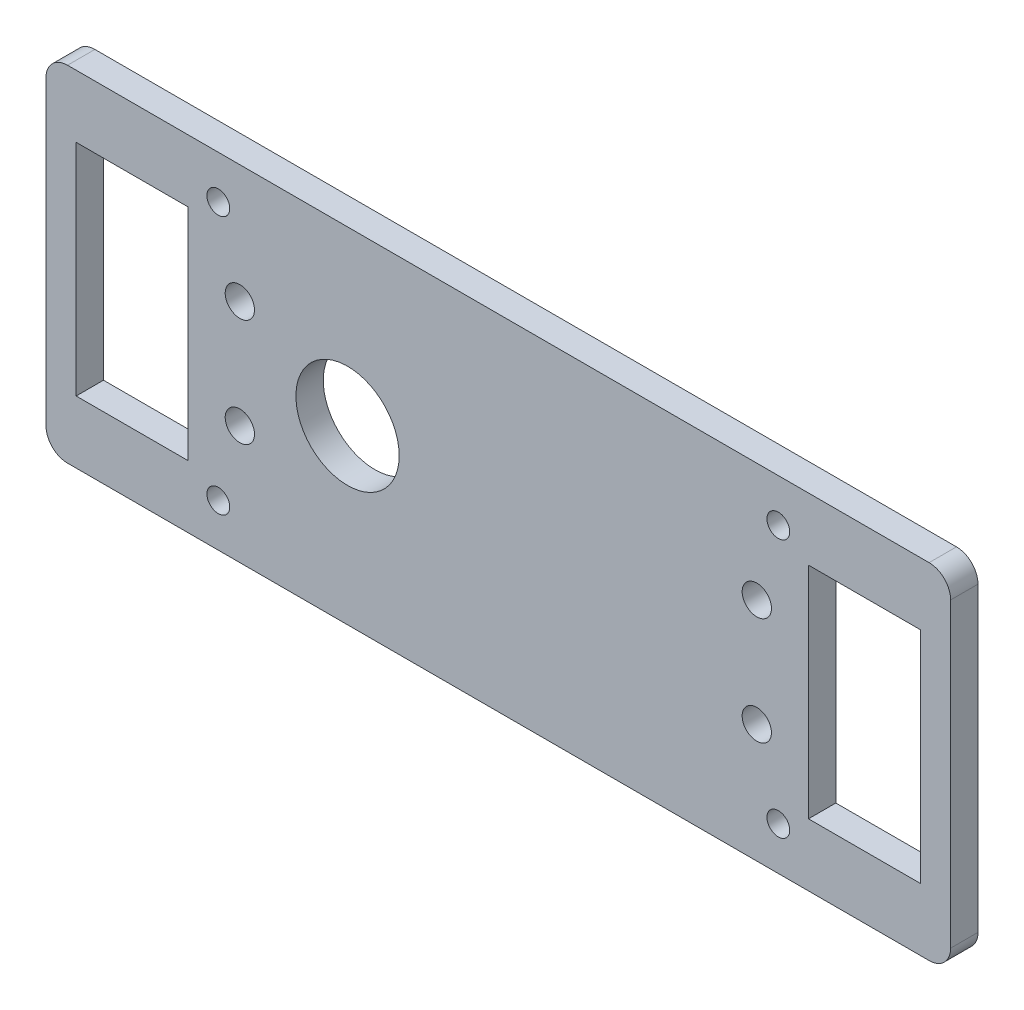
SolidWorks part; units mm, degrees
material "5052-H32"
ref_plane "Front Plane" through (0, 0, 0) normal (0, 0, 1) x (1, 0, 0)
ref_plane "Top Plane" through (0, 0, 0) normal (0, 1, 0) x (1, 0, 0)
ref_plane "Right Plane" through (0, 0, 0) normal (1, 0, 0) x (0, 0, -1)
sketch "Sketch1" plane through (0, 0, 0) normal (0, 0, 1) x (1, 0, 0)
  line L0 (-30, 30) -> (100, 30) construction
  line L1 (-70, 40) -> (140, 40)
  line L2 (-70, 40) -> (-70, -40)
  line L3 (-70, -40) -> (140, -40)
  line L4 (140, 40) -> (140, -40)
  line L5 (-30, 30) -> (-30, -30) construction
  line L6 (35.3553, -35.3553) -> (0, 0) construction
  line L7 (-50, 12.5) -> (120, 12.5) construction
  line L8 (-50, 12.5) -> (-50, -12.5) construction
  line L9 (-50, -12.5) -> (120, -12.5) construction
  line L10 (120, 12.5) -> (120, -12.5) construction
  line L11 (0, 0) -> (50, 0) construction
  line L13 (-63, 25.5) -> (-37, 25.5)
  line L14 (-63, 25.5) -> (-63, -25.5)
  line L15 (-63, -25.5) -> (-37, -25.5)
  line L16 (-37, 25.5) -> (-37, -25.5)
  line L17 (107, 25.5) -> (133, 25.5)
  line L18 (107, 25.5) -> (107, -25.5)
  line L19 (107, -25.5) -> (133, -25.5)
  line L20 (133, 25.5) -> (133, -25.5)
  circle A0 centre (0, 0) radius 11.9875
  circle A1 centre (-30, 30) radius 2.5 construction
  circle A2 centre (100, 30) radius 2.5 construction
  circle A3 centre (-30, -30) radius 2.5 construction
  circle A4 centre (100, -30) radius 2.5 construction
  circle A5 centre (-50, 12.5) radius 4 construction
  circle A6 centre (-50, -12.5) radius 4 construction
  circle A7 centre (120, -12.5) radius 4 construction
  circle A8 centre (120, 12.5) radius 4 construction
  circle A9 centre (50, 0) radius 40 construction
  arc A10 (50, 0) -> (35.3553, -35.3553) centre (0, 0) cw construction
  circle A11 centre (35.3553, -35.3553) radius 40 construction
  circle A12 centre (-25, 12.5) radius 4 construction
  circle A13 centre (-25, -12.5) radius 4 construction
  circle A14 centre (95, 12.5) radius 4 construction
  circle A15 centre (95, -12.5) radius 4 construction
  point P20 (-50, 0)
  point P28 (-30, 0)
  point P31 (-70, 0)
  point P32 (35, 40)
  point P34 (35, 12.5)
  point P41 (-50, 25.5)
  point P42 (-37, 0)
  point P43 (120, 25.5)
  point P52 (0, 0)
  point P53 (0, 0)
  point P54 (-50, 12.5)
  dimension "D1" = 23.975
  dimension "D6" = 60
  dimension "D7" = 5
  dimension "D2" = 8
  dimension "D9" = 20
  dimension "D11" = 80
  dimension "D12" = 50
  dimension "D17" = 8
  dimension "D18" = 25
  dimension "D19" = 25
  dimension "D3" = 20
  dimension "D4" = 130
  dimension "D5" = 10
  dimension "D8" = 30
  dimension "D10" = 25
  dimension "D13" = 45
  dimension "D14" = 20
  dimension "D15" = 51
  dimension "D16" = 26
extrude "Boss-Extrude1" add sketch "Sketch1" against normal blind 6.35 contours L1 L4 L3 L2
hole_wizard "M5 Clearance Hole1" positions "3DSketch1" profile "Sketch2" hole size "M5" standard "ANSI Metric" end condition up to next
sketch3d "3DSketch1"
  point P0 (-30, 30, 0)
  point P2 (-30, -30, 0)
  point P4 (100, -30, 0)
  point P6 (100, 30, 0)
sketch "Sketch2" plane through (-30, 30, 0) normal (1, 0, 0) x (0, -1, 0)
  line L0 (0, 0) -> (0, 6.35)
  line L1 (0, 6.35) -> (2.65, 6.35)
  line L2 (2.65, 6.35) -> (2.65, 0)
  line L5 (2.65, 0) -> (0, 0)
  line L11 (0, -6.35) -> (0, 107.95) construction
  dimension "Thru Hole Dia." = 5.3
  dimension "Thru Hole Depth" = 6.35
fillet "Fillet1" radius 5 4 edges at (140, -40, -3.175) (140, 40, -3.175) (-70, -40, -3.175) (-70, 40, -3.175)
hole_wizard "Tap Drill for M8x1.25 Tap1" positions "3DSketch2" profile "Sketch3" hole size "M8x1.25" standard "ANSI Metric" end condition up to next
sketch3d "3DSketch2"
  point P18 (-25, 12.5, 0)
  point P20 (-25, -12.5, 0)
  point P22 (95, 12.5, 0)
  point P24 (95, -12.5, 0)
  point P27 (95, 12.5, 0)
  point P29 (95, -12.5, 0)
  point P31 (-25, -12.5, 0)
  point P33 (-25, 12.5, 0)
sketch "Sketch3" plane through (-25, 12.5, 0) normal (1, 0, 0) x (0, -1, 0)
  line L0 (0, 0) -> (0, 6.35)
  line L1 (0, 6.35) -> (3.4, 6.35)
  line L2 (3.4, 6.35) -> (3.4, 0)
  line L5 (3.4, 0) -> (0, 0)
  line L11 (0, -6.35) -> (0, 107.95) construction
  dimension "Thru Hole Dia." = 6.8
  dimension "Thru Hole Depth" = 6.35
